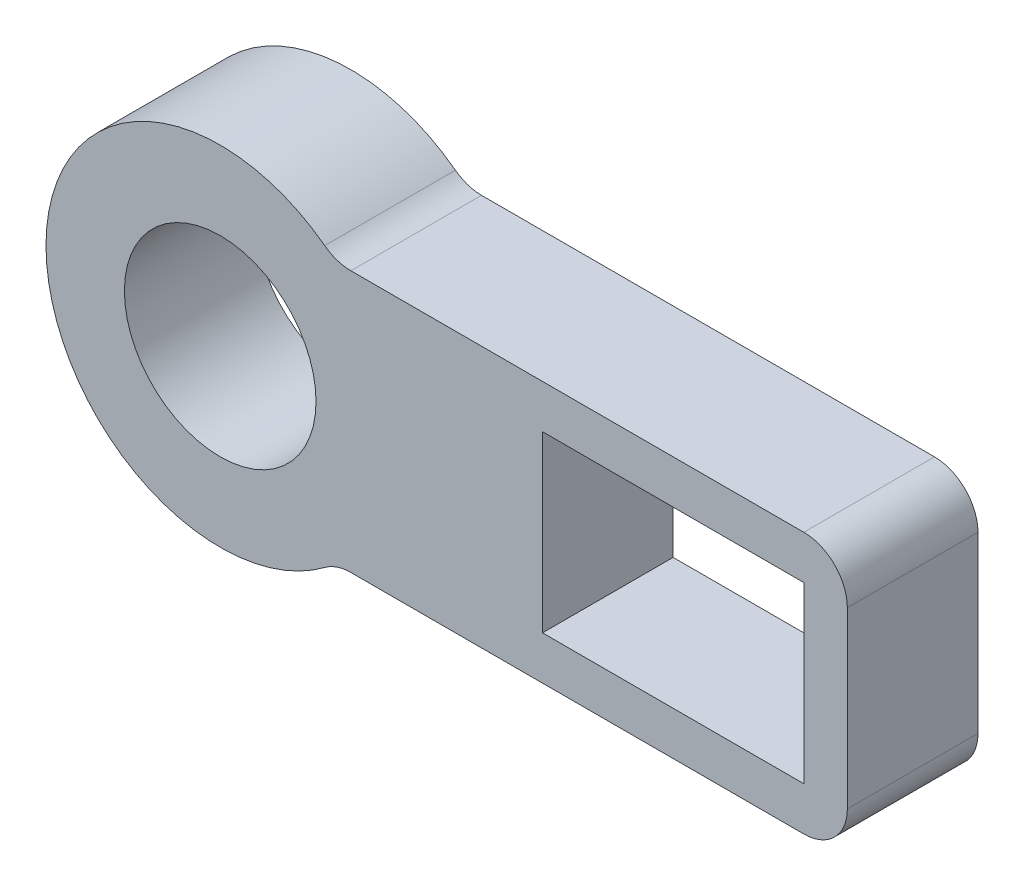
SolidWorks part; units mm, degrees
material "ABS"
ref_plane "Front Plane" through (0, 0, 0) normal (0, 0, 1) x (1, 0, 0)
ref_plane "Top Plane" through (0, 0, 0) normal (0, 1, 0) x (1, 0, 0)
ref_plane "Right Plane" through (0, 0, 0) normal (1, 0, 0) x (0, 0, -1)
sketch "Sketch1" plane through (0, 0, 0) normal (0, 0, 1) x (1, 0, 0)
  line L0 (0, 0) -> (18.288, 0) construction
  line L1 (3.3601, 3.81) -> (18.288, 3.81)
  line L2 (18.288, 3.81) -> (18.288, -3.81)
  line L3 (18.288, -3.81) -> (3.3601, -3.81)
  line L5 (9.398, 2.54) -> (17.018, 2.54)
  line L6 (9.398, 2.54) -> (9.398, -2.54)
  line L7 (9.398, -2.54) -> (17.018, -2.54)
  line L8 (17.018, 2.54) -> (17.018, -2.54)
  circle A0 centre (0, 0) radius 2.794
  arc A1 (3.3601, 3.81) -> (3.3601, -3.81) centre (0, 0) ccw
  point P7 (18.288, 0)
  point P13 (9.398, 0)
  point P14 (13.208, 2.54)
  dimension "D1" = 5.588
  dimension "D2" = 10.16
  dimension "D3" = 1.27
  dimension "D4" = 7.62
  dimension "D5" = 5.08
  dimension "D6" = 7.62
  dimension "D7" = 13.208
extrude "Boss-Extrude1" add sketch "Sketch1" along normal mid plane 3.81
fillet "Fillet1" radius 1.27 4 edges at (3.3601, -3.81, 0) (3.3601, 3.81, 0) (18.288, -3.81, 0) (18.288, 3.81, 0)
